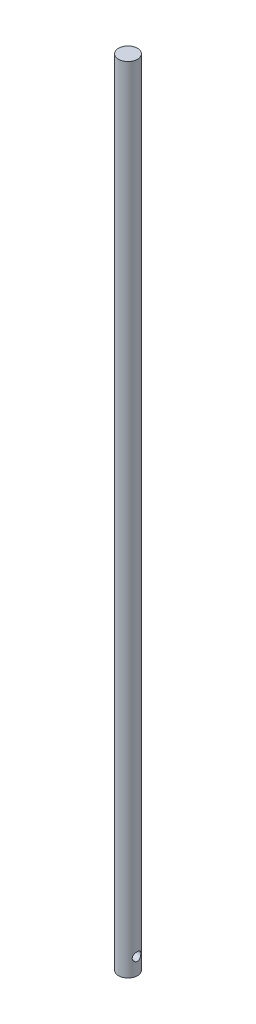
SolidWorks part; units mm, degrees
ref_plane "前视基准面" through (0, 0, 0) normal (0, 0, 1) x (1, 0, 0)
ref_plane "上视基准面" through (0, 0, 0) normal (0, 1, 0) x (1, 0, 0)
ref_plane "右视基准面" through (0, 0, 0) normal (1, 0, 0) x (0, 0, -1)
other "Configuration Table"
sketch "草图1" plane through (0, 0, 0) normal (0, 1, 0) x (1, 0, 0)
  circle A0 centre (0, 0) radius 3
  dimension "D1" = 6
extrude "凸台-拉伸1" add sketch "草图1" along normal blind 250
ref_plane "基准面1" through (3, 0, 0) normal (1, 0, 0) x (0, 0, -1)
sketch "草图2" plane through (3, 0, 0) normal (1, 0, 0) x (0, 0, -1)
  line L0 (0, 5.2657) -> (0, 0) construction
  circle A0 centre (0, 5.2657) radius 1.35
  dimension "D1" = 2.7
extrude "切除-拉伸1" cut sketch "草图2" against normal through all
